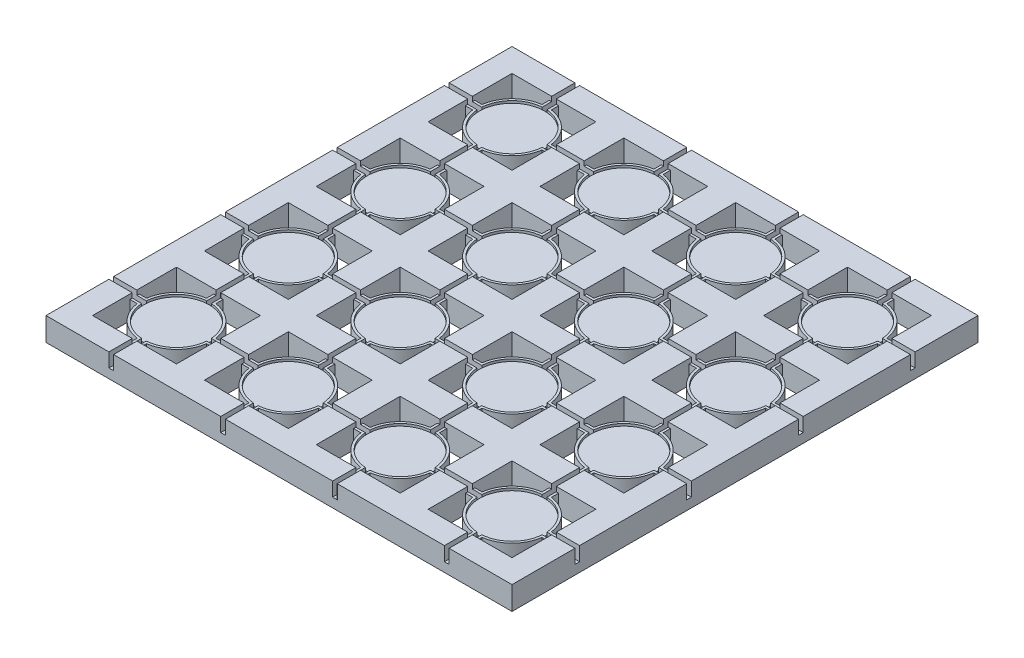
SolidWorks part; units mm, degrees
ref_plane "Front Plane" through (0, 0, 0) normal (0, 0, 1) x (1, 0, 0)
ref_plane "Top Plane" through (0, 0, 0) normal (0, 1, 0) x (1, 0, 0)
ref_plane "Right Plane" through (0, 0, 0) normal (1, 0, 0) x (0, 0, -1)
sketch "Sketch1" plane through (0, 0, 0) normal (0, 1, 0) x (1, 0, 0)
  line L6 (-100, -100) -> (100, -100)
  line L11 (-100, -100) -> (-100, 100)
  line L12 (-100, 100) -> (100, 100)
  line L76 (100, -100) -> (100, 100)
  line L77 (-100, -100) -> (100, 100) construction
  line L78 (-100, 100) -> (100, -100) construction
  point P0 (0, 0)
  dimension "D1" = 200
extrude "Boss-Extrude1" add sketch "Sketch1" along normal blind 10
sketch "Sketch2" plane through (0, 10, 0) normal (0, 1, 0) x (1, 0, 0)
  line L0 (-100, 100) -> (100, -100) construction
  line L1 (-100, 100) -> (-100, -100) construction
  line L2 (-90, 54) -> (-54, 54)
  line L3 (-90, 54) -> (-90, 90)
  line L4 (-90, 90) -> (-54, 90)
  line L5 (-54, 54) -> (-54, 90)
  line L6 (-90, 54) -> (-54, 90) construction
  line L7 (-90, 90) -> (-54, 54) construction
  line L8 (-57, 72) -> (-54, 72) construction
  line L9 (-57.1339, 70) -> (-54, 70)
  line L10 (-57.1339, 74) -> (-54, 74)
  line L11 (-57, 74) -> (-54, 74) construction
  line L12 (-57, 70) -> (-54, 70) construction
  line L13 (-70, 57.1339) -> (-70, 54)
  line L14 (-74, 57.1339) -> (-74, 54)
  line L15 (-86.8661, 70) -> (-90, 70)
  line L16 (-86.8661, 74) -> (-90, 74)
  line L17 (-74, 86.8661) -> (-74, 90)
  line L18 (-70, 86.8661) -> (-70, 90)
  arc A0 (-74, 86.8661) -> (-86.8661, 74) centre (-72, 72) ccw
  arc A1 (-86.8661, 70) -> (-74, 57.1339) centre (-72, 72) ccw
  arc A2 (-70, 57.1339) -> (-57.1339, 70) centre (-72, 72) ccw
  arc A3 (-57.1339, 74) -> (-70, 86.8661) centre (-72, 72) ccw
  point P4 (-72, 72)
  dimension "D3" = 30
  dimension "D1" = 36
  dimension "D2" = 10
  dimension "D4" = 2
  dimension "D5" = 2
  dimension "D6" = 4
extrude "Cut-Extrude2" cut sketch "Sketch2" against normal through all contours A3 L10 L5 L4 L18 | A2 L13 L2 L5 L9 | A1 L15 L3 L2 L14 | A0 L17 L4 L3 L16
sketch "Sketch3" plane through (0, 10, 0) normal (0, 1, 0) x (1, 0, 0)
  line L1 (-90, 90) -> (-54, 90)
  line L2 (-90, 90) -> (-90, 54)
  line L3 (-90, 54) -> (-54, 54)
  line L4 (-54, 90) -> (-54, 54)
extrude "Cut-Extrude3" cut sketch "Sketch3" against normal blind 2
sketch "Sketch4" plane through (0, 8, 0) normal (0, 1, 0) x (1, 0, 0)
  circle A0 centre (-72, 72) radius 14
  dimension "D1" = 28
extrude "Cut-Extrude4" cut sketch "Sketch4" against normal blind 1
sketch "Sketch5" plane through (0, 10, 0) normal (0, 1, 0) x (1, 0, 0)
  line L0 (-100, 72) -> (-86, 72) construction
  line L1 (-100, 100) -> (-100, -100) construction
  line L2 (-72, 100) -> (-72, 86) construction
  line L3 (100, 100) -> (-100, 100) construction
  line L5 (-90, 90) -> (-54, 90) construction
  line L7 (-90, 74) -> (-90, 70) construction
  line L8 (-73, 100) -> (-73, 85.9642)
  line L9 (-100, 71) -> (-85.9642, 71)
  line L10 (-71, 100) -> (-71, 85.9642)
  line L11 (-100, 73) -> (-85.9642, 73)
  line L12 (-73, 100) -> (-71, 100)
  line L14 (-100, 71) -> (-100, 73)
  line L16 (-58.0358, 73) -> (-44, 73)
  line L17 (-100, 73) -> (100, 73) construction
  line L18 (-58, 72) -> (-44, 72) construction
  line L19 (-100, 72) -> (100, 72) construction
  line L20 (-58.0358, 71) -> (-44, 71)
  line L21 (-100, 71) -> (100, 71) construction
  line L22 (-71, 58.0358) -> (-71, 44)
  line L23 (-71, 100) -> (-71, -100) construction
  line L24 (-72, 58) -> (-72, 44) construction
  line L25 (-72, 100) -> (-72, -100) construction
  line L26 (-73, 58.0358) -> (-73, 44)
  line L27 (-73, 100) -> (-73, -100) construction
  line L28 (-54, 54) -> (-54, 90) construction
  line L29 (-73, 100) -> (-71, 100)
  line L32 (-100, 73) -> (-100, 71)
  line L33 (-73, 44) -> (-71, 44)
  line L34 (-44, 73) -> (-44, 71)
  line L35 (-90, 54) -> (-54, 54) construction
  circle A0 centre (-72, 72) radius 14 construction
  arc A1 (-71, 85.9642) -> (-73, 85.9642) centre (-72, 72) ccw
  arc A2 (-85.9642, 73) -> (-85.9642, 71) centre (-72, 72) ccw
  arc A3 (-58.0358, 71) -> (-58.0358, 73) centre (-72, 72) ccw
  arc A4 (-73, 58.0358) -> (-71, 58.0358) centre (-72, 72) ccw
  point P9 (-72, 90)
  point P17 (-90, 72)
  line M4 (100, 100) -> (-100, 100)
  line M5 (-100, 100) -> (-100, -100)
  line M7 (-54, 54) -> (-90, 54)
  line M8 (-90, 54) -> (-90, 90)
  line M9 (-90, 90) -> (-54, 90)
  line M10 (-54, 90) -> (-54, 54)
  dimension "D1" = 0
  dimension "D2" = 1
  dimension "D4" = 10
  dimension "D5" = 10
  dimension "D3" = 1
extrude "Cut-Extrude5" cut sketch "Sketch5" against normal blind 6 contours L26 L33 L22 M7 | A4 L26 L22 M7 | L34 L16 L20 M10 | A3 L20 L16 M10 | A1 L10 L8 M9 | L10 L8 M4 M9 | L11 L9 M5 M8 | A2 L11 L9 M8
pattern_linear "LPattern2" count 4 spacing 48 along (1, 0, 0) count 4 spacing 48 along (0, 0, 1) of "Cut-Extrude2", "Cut-Extrude3", "Cut-Extrude4", "Cut-Extrude5"
sketch "Sketch6" plane through (0, 0, 0) normal (0, -1, 0) x (1, 0, 0)
  line L1 (-90, 90) -> (-54, 90)
  line L2 (-90, 90) -> (-90, 54)
  line L3 (-90, 54) -> (-54, 54)
  line L4 (-54, 90) -> (-54, 54)
extrude "Cut-Extrude6" cut sketch "Sketch6" against normal blind 2
pattern_linear "LPattern3" count 4 spacing 48 along (0, 0, -1) count 4 spacing 48 along (1, 0, 0) of "Cut-Extrude6"
